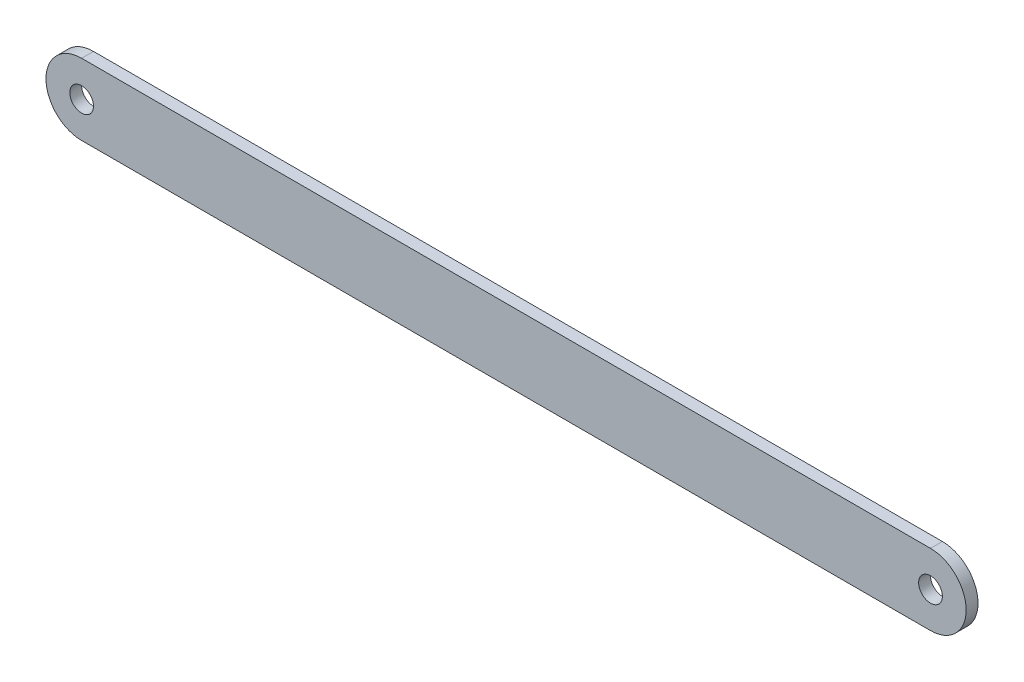
SolidWorks part; units mm, degrees
ref_plane "Plan de face" through (0, 0, 0) normal (0, 0, 1) x (1, 0, 0)
ref_plane "Plan de dessus" through (0, 0, 0) normal (0, 1, 0) x (1, 0, 0)
ref_plane "Plan de droite" through (0, 0, 0) normal (1, 0, 0) x (0, 0, -1)
sketch "Esquisse1" plane through (0, 0, 0) normal (0, 0, 1) x (1, 0, 0)
  line L0 (-71.5, 0) -> (71.5, 0) construction
  line L1 (-71.5, 6) -> (71.5, 6)
  line L2 (-71.5, -6) -> (71.5, -6)
  arc A0 (-71.5, 6) -> (-71.5, -6) centre (-71.5, 0) ccw
  arc A1 (71.5, -6) -> (71.5, 6) centre (71.5, 0) ccw
  circle A2 centre (-71.5, 0) radius 2
  circle A3 centre (71.5, 0) radius 2
  point P2 (0, 0)
  point P12 (0, 0)
  point P13 (0, 0)
  point P16 (55.4153, 38.3571)
  dimension "D1" = 6
  dimension "D2" = 4
  dimension "D3" = 4
  dimension "D4" = 71.5
extrude "Boss.-Extru.1" add sketch "Esquisse1" along normal blind 2
